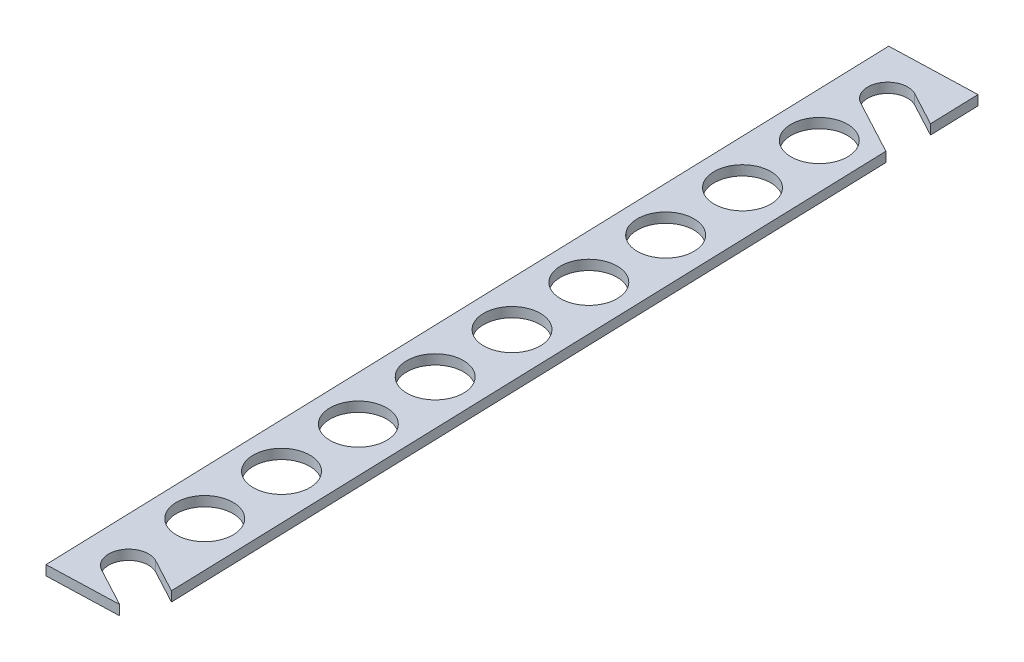
SolidWorks part; units mm, degrees
material "6061-T6 (SS)"
ref_plane "Front" through (0, 0, 0) normal (0, 0, 1) x (1, 0, 0)
ref_plane "Top" through (0, 0, 0) normal (0, 1, 0) x (1, 0, 0)
ref_plane "Right" through (0, 0, 0) normal (1, 0, 0) x (0, 0, -1)
sketch "Sketch1" plane through (0, 0, 0) normal (0, 1, 0) x (1, 0, 0)
  line B0 (6.7764, -70.1992) -> (-4.7647, -70.5654)
  line B1 (4.7647, 70.5654) -> (-9.2283, 70.1214)
  line B2 (-9.2283, 70.1214) -> (-4.7647, -70.5654)
  line B3 (4.7647, 70.5654) -> (5.0164, 62.6327)
  line B4 (-2.2318, 70.3434) -> (-1.6277, 51.303) construction
  line B5 (2.2318, -70.3434) -> (1.6277, -51.303) construction
  line B6 (-0.4907, 65.5258) -> (5.0182, 62.5741) construction
  line B7 (-3.4897, 59.9286) -> (5.2507, 55.2454) construction
  line B8 (3.5299, -61.198) -> (9.0388, -64.1497) construction
  line B9 (0.5309, -66.7952) -> (6.878, -70.196) construction
  line B10 (5.2526, 55.1868) -> (9.037, -64.091)
  line B11 (-0.4667, 65.5706) -> (5.0164, 62.6327)
  line B12 (-3.5137, 59.8838) -> (5.2526, 55.1868)
  line B13 (3.5539, -61.1532) -> (9.037, -64.091)
  line B14 (0.5069, -66.8399) -> (6.7764, -70.1992)
  arc B15 (3.5299, -61.198) -> (0.5309, -66.7952) centre (2.0304, -63.9966) ccw construction
  arc B16 (-0.4907, 65.5258) -> (-3.4897, 59.9286) centre (-1.9902, 62.7272) ccw construction
  circle B17 centre (-1.6277, 51.303) radius 4.572
  circle B18 centre (-1.2208, 38.4772) radius 4.572
  circle B19 centre (-0.8138, 25.6515) radius 4.572
  circle B20 centre (-0.4069, 12.8257) radius 4.572
  circle B21 centre (0, 0) radius 4.572
  circle B22 centre (0.4069, -12.8257) radius 4.572
  circle B23 centre (0.8138, -25.6515) radius 4.572
  circle B24 centre (1.2208, -38.4772) radius 4.572
  circle B25 centre (1.6277, -51.303) radius 4.572
  arc B26 (-0.4667, 65.5706) -> (-3.5137, 59.8838) centre (-1.9902, 62.7272) ccw
  arc B27 (3.5539, -61.1532) -> (0.5069, -66.8399) centre (2.0304, -63.9966) ccw
sketch_block_instance "Block1-1"
sketch_block "Block1" parameters "D1"=4.572, "D2"=19.05, "D3"=30
extrude "Boss-Extrude1" add sketch "Sketch1" along normal blind 1.5875
